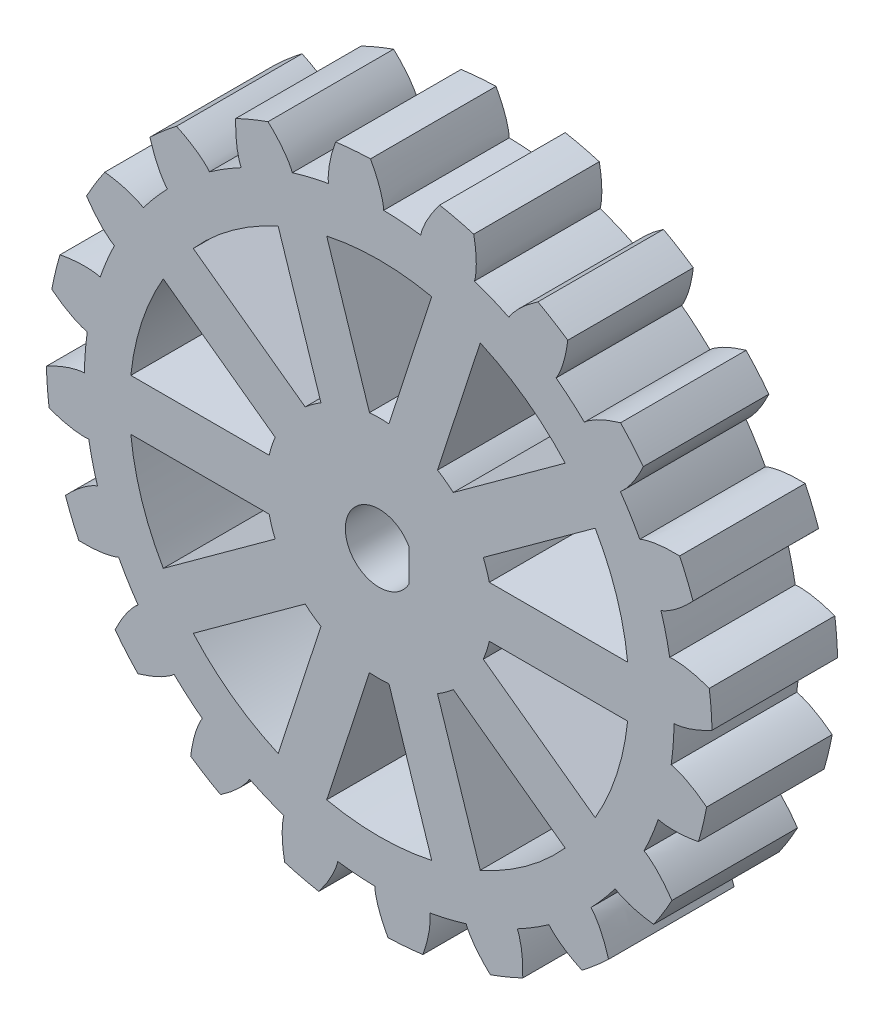
SolidWorks part; units mm, degrees
ref_plane "Front Plane" through (0, 0, 0) normal (0, 0, 1) x (1, 0, 0)
ref_plane "Top Plane" through (0, 0, 0) normal (0, 1, 0) x (1, 0, 0)
ref_plane "Right Plane" through (0, 0, 0) normal (1, 0, 0) x (0, 0, -1)
sketch "Sketch6" plane through (0, 0, 0) normal (0, 0, 1) x (1, 0, 0)
  line L0 (87.6899, 36.827) -> (87.6899, 90.4407) construction
  line L1 (87.6899, 61.8261) -> (62.7181, 61.8261) construction
  line L2 (87.6899, 61.8261) -> (56.3004, 50.4013) construction
  line L3 (79.6554, 58.9018) -> (87.6899, 61.8261) construction
  line L4 (77.8074, 58.1386) -> (87.3788, 62.5771) construction
  line L5 (76.0304, 57.2208) -> (86.9259, 63.45) construction
  line L6 (74.338, 56.1551) -> (86.3097, 64.4252) construction
  line L7 (81.5622, 59.5052) -> (87.8859, 61.2139) construction
  line L8 (83.5134, 59.9442) -> (87.9914, 60.7533) construction
  line L9 (85.4949, 60.2157) -> (88.0342, 60.454) construction
  line L10 (87.4923, 60.3177) -> (88.0428, 60.3223) construction
  line L11 (88.0428, 60.3223) -> (88.0425, 60.3158) construction
  line L12 (88.0425, 60.3158) -> (88.0425, 60.3094) construction
  line L13 (87.6899, 36.827) -> (85.2614, 67.5128) construction
  line L14 (111.173, 36.827) -> (112.6899, 36.827) construction
  line L15 (112.6899, 36.827) -> (114.2068, 36.827) construction
  circle A0 centre (87.6899, 36.827) radius 26.5169 construction
  circle A1 centre (87.6899, 36.827) radius 25 construction
  circle A2 centre (87.6899, 36.827) radius 23.4915 construction
  arc A3 (79.6554, 58.9018) -> (77.8074, 58.1386) centre (87.6899, 36.827) ccw construction
  arc A4 (77.8074, 58.1386) -> (76.0304, 57.2208) centre (87.6899, 36.827) ccw construction
  arc A5 (76.0304, 57.2208) -> (74.338, 56.1551) centre (87.6899, 36.827) ccw construction
  arc A6 (79.6554, 58.9018) -> (81.5622, 59.5052) centre (87.6899, 36.827) cw construction
  arc A7 (81.5622, 59.5052) -> (83.5134, 59.9442) centre (87.6899, 36.827) cw construction
  arc A8 (83.5134, 59.9442) -> (85.4949, 60.2157) centre (87.6899, 36.827) cw construction
  arc A9 (85.4949, 60.2157) -> (87.4923, 60.3177) centre (87.6899, 36.827) cw construction
  circle A10 centre (87.6899, 36.827) radius 23.485 construction
  spline S0 degree 3 poles (88.0425, 60.3094) (88.0393, 60.4586) (87.9965, 60.763) (87.8787, 61.2705) (87.6796, 61.8825) (87.2187, 62.9893) (86.7132, 63.8389) (86.3097, 64.4252) knots 0 0 0 0 0.099096 0.20382 0.346132 0.526411 1 1 1 1 construction
  spline S1 degree 3 poles (83.648, 59.9616) (83.6277, 60.1095) (83.6221, 60.4168) (83.6586, 60.9366) (83.759, 61.5723) (84.04, 62.7378) (84.4056, 63.6562) (84.7119, 64.2988) knots 0 0 0 0 0.099096 0.20382 0.346132 0.526411 1 1 1 1 construction
  point P7 (79.6554, 58.9018)
  dimension "D2" = 50
  dimension "D4" = 2
  dimension "D7" = 2
  dimension "D13" = 2
  dimension "D17" = 2
  dimension "D3" = 20
  dimension "D5" = 8.5502
  dimension "D6" = 10.5505
  dimension "D8" = 12.5505
  dimension "D9" = 2
  dimension "D10" = 14.5505
  dimension "D11" = 2
  dimension "D12" = 6.5505
  dimension "D14" = 4.5505
  dimension "D15" = 2
  dimension "D16" = 2.5505
  dimension "D18" = 0.5505
  dimension "D19" = 4.525
sketch "Sketch7" plane through (0, 0, 0) normal (0, 0, 1) x (1, 0, 0)
  circle A0 centre (87.6899, 36.827) radius 23.485 construction
  circle A1 centre (87.6899, 36.827) radius 26.5169 construction
  arc A2 (88.0425, 60.3094) -> (83.648, 59.9616) centre (87.6899, 36.827) ccw construction
  arc A3 (86.9912, 63.3347) -> (84.2104, 63.1146) centre (87.6899, 36.827) ccw construction
  spline S0 degree 3 poles (-1911.6865, 35.1483) (71.5756, 40.4372) (89.8382, 52.8293) (87.8787, 61.2705) (87.6796, 61.8825) (75.5402, 91.0375) (-65.3864, 59.6539) (2084.1552, 156.0334) knots -5.410264 -5.410264 -5.410264 -5.410264 0.099096 0.20382 0.346132 0.526411 21.176223 21.176223 21.176223 21.176223 only from (88.0425, 60.3094) to (86.3097, 64.4252) construction
  spline S1 degree 3 poles (2062.4411, 349.6638) (103.0357, 42.927) (83.0512, 52.2922) (83.6586, 60.9366) (83.759, 61.5723) (91.1612, 92.2738) (235.27, 83.4481) (-1902.673, -159.4872) knots -5.410264 -5.410264 -5.410264 -5.410264 0.099096 0.20382 0.346132 0.526411 21.176223 21.176223 21.176223 21.176223 only from (83.648, 59.9616) to (84.7119, 64.2988) construction
  spline S2 degree 3 poles (88.0425, 60.3094) (88.0393, 60.4586) (87.9965, 60.763) (87.8787, 61.2705) (87.6796, 61.8825) (87.3837, 62.5931) (87.1297, 63.087) (86.9912, 63.3347) knots 0 0 0 0 0.099096 0.20382 0.346132 0.526411 0.715001 0.715001 0.715001 0.715001 construction
  spline S3 degree 3 poles (83.648, 59.9616) (83.6277, 60.1095) (83.6221, 60.4168) (83.6586, 60.9366) (83.759, 61.5723) (83.9394, 62.3206) (84.1125, 62.8482) (84.2104, 63.1146) knots 0 0 0 0 0.099096 0.20382 0.346132 0.526411 0.715001 0.715001 0.715001 0.715001 construction
sketch "Sketch11" plane through (0, 0, 0) normal (0, 0, 1) x (1, 0, 0)
  circle A0 centre (0, 0) radius 23.485
  dimension "D1" = 46.97
extrude "Boss-Extrude6" add sketch "Sketch11" along normal blind 10
sketch "Sketch12" plane through (0, 0, 10) normal (0, 0, 1) x (1, 0, 0)
  arc A2 (-0.6987, 26.5077) -> (-3.4795, 26.2876) centre (0, 0) ccw
  arc A3 (0.3526, 23.4824) -> (-4.0419, 23.1346) centre (0, 0) ccw
  spline S2 degree 3 poles (-4.0419, 23.1346) (-4.0622, 23.2824) (-4.0678, 23.5897) (-4.0313, 24.1095) (-3.9309, 24.7452) (-3.7505, 25.4935) (-3.5774, 26.0212) (-3.4795, 26.2876) knots 0 0 0 0 0.099096 0.20382 0.346132 0.526411 0.715001 0.715001 0.715001 0.715001
  spline S3 degree 3 poles (0.3526, 23.4824) (0.3494, 23.6316) (0.3066, 23.9359) (0.1887, 24.4435) (-0.0104, 25.0555) (-0.3062, 25.7661) (-0.5602, 26.26) (-0.6987, 26.5077) knots 0 0 0 0 0.099096 0.20382 0.346132 0.526411 0.715001 0.715001 0.715001 0.715001
extrude "Boss-Extrude7" add sketch "Sketch12" against normal blind 10
pattern_circular "CirPattern2" count 20 over 360 of "Boss-Extrude7"
sketch "Sketch13" plane through (0, 0, 10) normal (0, 0, 1) x (1, 0, 0)
  line L0 (2.45, 1.1347) -> (2.45, -1.1347)
  arc A0 (2.45, 1.1347) -> (2.45, -1.1347) centre (0, 0) ccw
  dimension "D1" = 5.4
  dimension "D2" = 2.45
extrude "Cut-Extrude2" cut sketch "Sketch13" against normal blind 10
sketch "Sketch14" plane through (0, 0, 0) normal (0, 0, -1) x (-1, 0, 0)
  line L1 (-7.3601, 2.8365) -> (-17.1995, 9.9851)
  line L2 (-7.6217, -2.0314) -> (-19.7838, -2.0314)
  line L4 (-7.6217, 2.0314) -> (-19.7838, 2.0314)
  line L8 (-4.972, 6.1234) -> (-14.8114, 13.2721)
  line L9 (-4.2873, 6.6209) -> (-8.0455, 18.1877)
  line L10 (-0.4232, 7.8764) -> (-4.1815, 19.4432)
  line L11 (0.4232, 7.8764) -> (4.1815, 19.4432)
  line L12 (4.2873, 6.6209) -> (8.0455, 18.1877)
  line L13 (4.972, 6.1234) -> (14.8114, 13.2721)
  line L14 (7.3601, 2.8365) -> (17.1995, 9.9851)
  line L15 (7.6217, 2.0314) -> (19.7838, 2.0314)
  line L16 (7.6217, -2.0314) -> (19.7838, -2.0314)
  line L17 (7.3601, -2.8365) -> (17.1995, -9.9851)
  line L18 (4.972, -6.1234) -> (14.8114, -13.2721)
  line L19 (4.2873, -6.6209) -> (8.0455, -18.1877)
  line L20 (0.4232, -7.8764) -> (4.1815, -19.4432)
  line L21 (-0.4232, -7.8764) -> (-4.1815, -19.4432)
  line L22 (-4.2873, -6.6209) -> (-8.0455, -18.1877)
  line L23 (-4.972, -6.1234) -> (-14.8114, -13.2721)
  line L24 (-7.3601, -2.8365) -> (-17.1995, -9.9851)
  circle A0 centre (0, 0) radius 19.8878 construction
  arc A1 (-4.1815, -19.4432) -> (4.1815, -19.4432) centre (0, 0) ccw
  circle A2 centre (0, 0) radius 22.8878 construction
  arc A3 (-0.4232, -7.8764) -> (0.4232, -7.8764) centre (0, 0) ccw
  circle A4 centre (0, 0) radius 7.8878 construction
  arc A5 (-4.972, -6.1234) -> (-4.2873, -6.6209) centre (0, 0) ccw
  arc A6 (-14.8114, -13.2721) -> (-8.0455, -18.1877) centre (0, 0) ccw
  arc A7 (4.2873, -6.6209) -> (4.972, -6.1234) centre (0, 0) ccw
  arc A8 (8.0455, -18.1877) -> (14.8114, -13.2721) centre (0, 0) ccw
  arc A9 (17.1995, -9.9851) -> (19.7838, -2.0314) centre (0, 0) ccw
  arc A10 (7.3601, -2.8365) -> (7.6217, -2.0314) centre (0, 0) ccw
  arc A11 (7.6217, 2.0314) -> (7.3601, 2.8365) centre (0, 0) ccw
  arc A12 (19.7838, 2.0314) -> (17.1995, 9.9851) centre (0, 0) ccw
  arc A13 (4.972, 6.1234) -> (4.2873, 6.6209) centre (0, 0) ccw
  arc A14 (14.8114, 13.2721) -> (8.0455, 18.1877) centre (0, 0) ccw
  arc A15 (0.4232, 7.8764) -> (-0.4232, 7.8764) centre (0, 0) ccw
  arc A16 (4.1815, 19.4432) -> (-4.1815, 19.4432) centre (0, 0) ccw
  arc A17 (-4.2873, 6.6209) -> (-4.972, 6.1234) centre (0, 0) ccw
  arc A18 (-8.0455, 18.1877) -> (-14.8114, 13.2721) centre (0, 0) ccw
  arc A19 (-7.3601, 2.8365) -> (-7.6217, 2.0314) centre (0, 0) ccw
  arc A20 (-17.1995, 9.9851) -> (-19.7838, 2.0314) centre (0, 0) ccw
  arc A21 (-19.7838, -2.0314) -> (-17.1995, -9.9851) centre (0, 0) ccw
  arc A22 (-7.6217, -2.0314) -> (-7.3601, -2.8365) centre (0, 0) ccw
  point P8 (-13.8878, 0)
  point P56 (0, 0)
  dimension "D1" = 3
  dimension "D2" = 12
  dimension "D3" = 10
extrude "Cut-Extrude3" cut sketch "Sketch14" against normal through all
sketch "Sketch16" plane through (0, 0, 0) normal (0, 0, -1) x (-1, 0, 0)
  line L0 (-2.45, -1.1347) -> (-2.45, 1.1347) construction
  line L1 (-2.45, -1.1347) -> (-2.45, 1.1347) construction
  line L2 (-2.375, 1.2843) -> (-2.375, -1.2843)
  arc A0 (-2.45, -1.1347) -> (-2.45, 1.1347) centre (0, 0) ccw construction
  arc A1 (-2.375, -1.2843) -> (-2.375, 1.2843) centre (0, 0) ccw
  circle A2 centre (0, 0) radius 9
  dimension "D1" = 18
  dimension "D2" = 0.15
extrude "Boss-Extrude9" add sketch "Sketch16" along normal blind 10 and the other way up to surface
sketch "Sketch17" plane through (2.375, 0, 0) normal (-1, 0, 0) x (0, 0, 1)
  line L1 (-10, 1.2843) -> (-10, -1.2843) construction
  circle A0 centre (-5, 0) radius 1
  point P6 (-10, 0)
  dimension "D1" = 2
  dimension "D2" = 5
extrude "Cut-Extrude4" cut sketch "Sketch17" against normal blind 20
